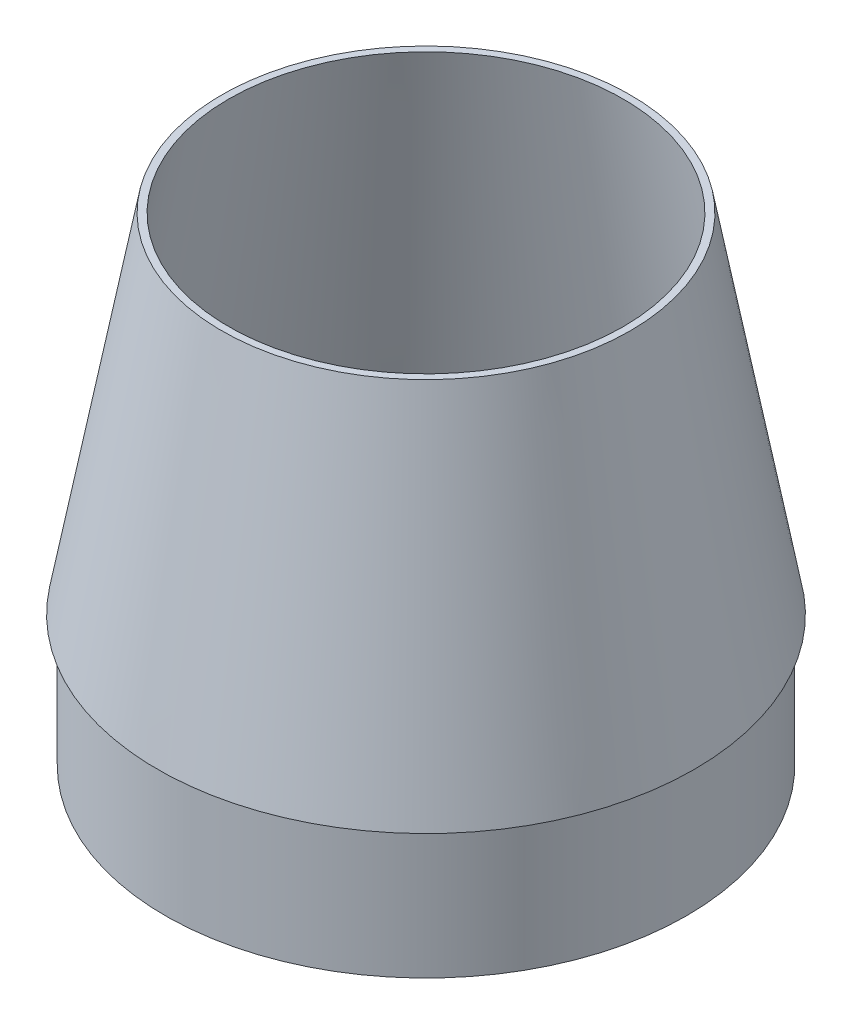
SolidWorks part; units mm, degrees
ref_plane "Front Plane" through (0, 0, 0) normal (0, 0, 1) x (1, 0, 0)
ref_plane "Top Plane" through (0, 0, 0) normal (0, 1, 0) x (1, 0, 0)
ref_plane "Right Plane" through (0, 0, 0) normal (1, 0, 0) x (0, 0, -1)
sketch "Sketch1" plane through (0, 0, 0) normal (0, 0, 1) x (1, 0, 0)
  line L0 (0, 139.7) -> (0, 0) construction
  line L1 (0, 139.7) -> (59.6773, 139.7)
  line L2 (59.6773, 139.7) -> (78.359, 38.1)
  line L3 (76.1619, 38.1) -> (76.1619, 0)
  line L4 (78.359, 38.1) -> (76.1619, 38.1)
  line L5 (76.1619, 0) -> (0, 0)
  line L6 (0, 0) -> (0, 139.7)
  dimension "D3" = 101.6
  dimension "D1" = 119.3546
  dimension "D2" = 156.718
  dimension "D4" = 38.1
  dimension "D5" = 152.3238
revolve "Revolve1" add sketch "Sketch1" angle 360 about L6
shell "Shell1" thickness 2.032
equation "\"Fore Diameter\"= 6.17"
equation "\"Aft Diameter\"= 4.62 + 0.079"
equation "\"Length\"= 4"
equation "\"Wall Thickness\"= 0.079"
equation "\"D3@Sketch1\"=\"Length\""
equation "\"D1@Sketch1\"=\"Aft Diameter\""
equation "\"D2@Sketch1\"=\"Fore Diameter\""
equation "\"Shoulder Diameter\"= 5.997"
equation "\"Shoulder Length\"= 1.5"
equation "\"D4@Sketch1\"=\"Shoulder Length\""
equation "\"D5@Sketch1\"=\"Shoulder Diameter\""
